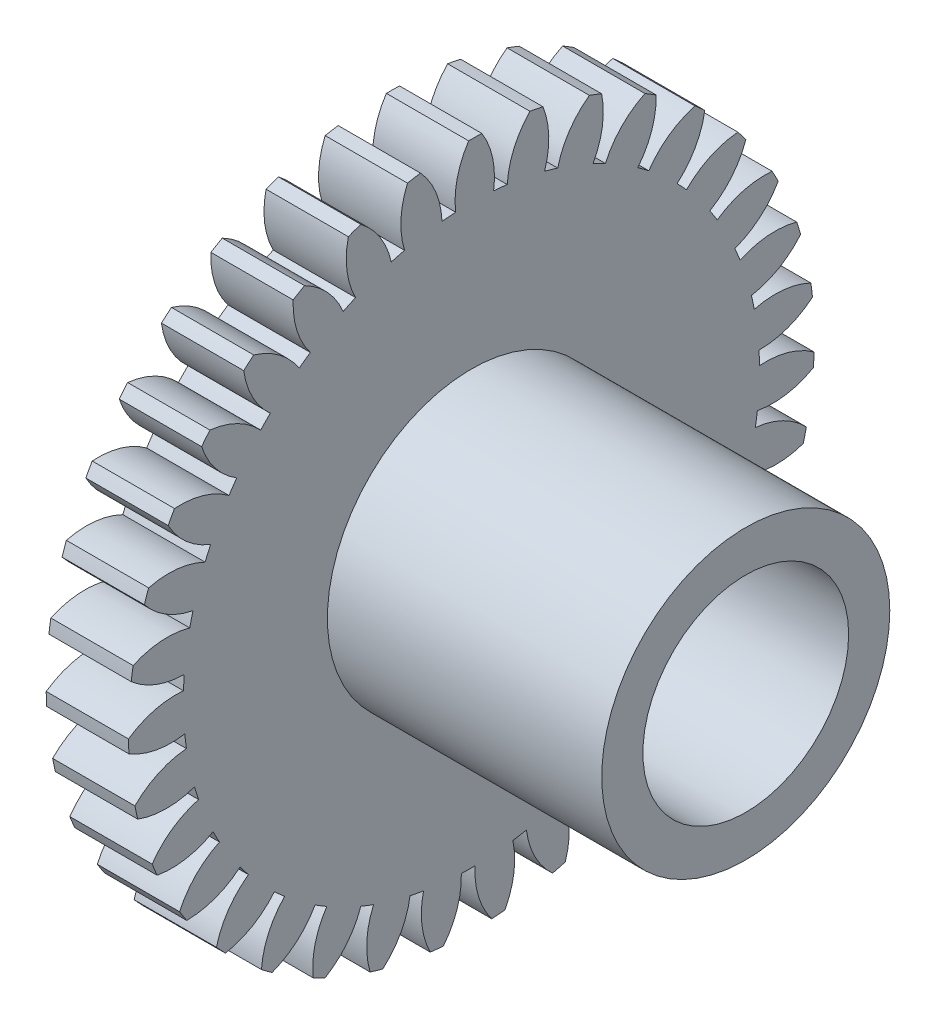
SolidWorks part; units mm, degrees
ref_plane "Front Plane" through (0, 0, 0) normal (0, 0, 1) x (1, 0, 0)
ref_plane "Top Plane" through (0, 0, 0) normal (0, 1, 0) x (1, 0, 0)
ref_plane "Right Plane" through (0, 0, 0) normal (1, 0, 0) x (0, 0, -1)
sketch "Sketch1" plane through (0, 0, 0) normal (0, 0, 1) x (1, 0, 0)
  line L0 (0, 0) -> (-14.1401, 0) construction
  line L1 (0, 3.75) -> (-13, 3.75)
  line L2 (-13, 3.75) -> (-13, 12.5)
  line L3 (-13, 12.5) -> (-10, 12.5)
  line L4 (-10, 12.5) -> (-10, 5.25)
  line L5 (-10, 5.25) -> (0, 5.25)
  line L6 (0, 5.25) -> (0, 3.75)
  dimension "D1" = 10
  dimension "D2" = 1.5
  dimension "D3" = 7.5
  dimension "D4" = 3
  dimension "D5" = 25
revolve "Revolve1" add sketch "Sketch1" angle 360 about L0
sketch "Sketch2" plane through (-13, 0, 0) normal (-1, 0, 0) x (0, 0, 1)
  line L0 (0, 0) -> (0, 12.5) construction
  line L1 (0.9807, 12.4615) -> (0, 0) construction
  circle A0 centre (0, 0) radius 12.5 construction
  arc A1 (0.1, 12.4996) -> (0.5744, 10.4843) centre (-2.4036, 10.8468) cw
  arc A2 (1.0728, 10.4451) -> (0.5744, 10.4843) centre (0, 0) ccw
  arc A3 (1.8566, 12.3614) -> (1.0728, 10.4451) centre (4.0709, 10.3372) ccw
  arc A4 (1.8566, 12.3614) -> (0.1, 12.4996) centre (0, 0) ccw
  arc A5 (0, 10.5) -> (1.0728, 10.4451) centre (0, 0) ccw construction
  arc A6 (0.5744, 10.4843) -> (0, 10.5) centre (0, 0) ccw construction
  arc A7 (0.1, 12.4996) -> (0, 12.5) centre (0, 0) ccw construction
  arc A8 (0, 12.5) -> (1.8566, 12.3614) centre (0, 0) ccw construction
  point P10 (0.8238, 10.4676)
  dimension "D1" = 21
  dimension "D2" = 3
  dimension "D3" = 0.1
  dimension "D4" = 4.5
  dimension "D5" = 0.25
extrude "Cut-Extrude1" cut sketch "Sketch2" against normal through all
pattern_circular "CirPattern1" count 35 over 360 about axis through (0, 0, 0) along (1, 0, 0) of "Cut-Extrude1"
